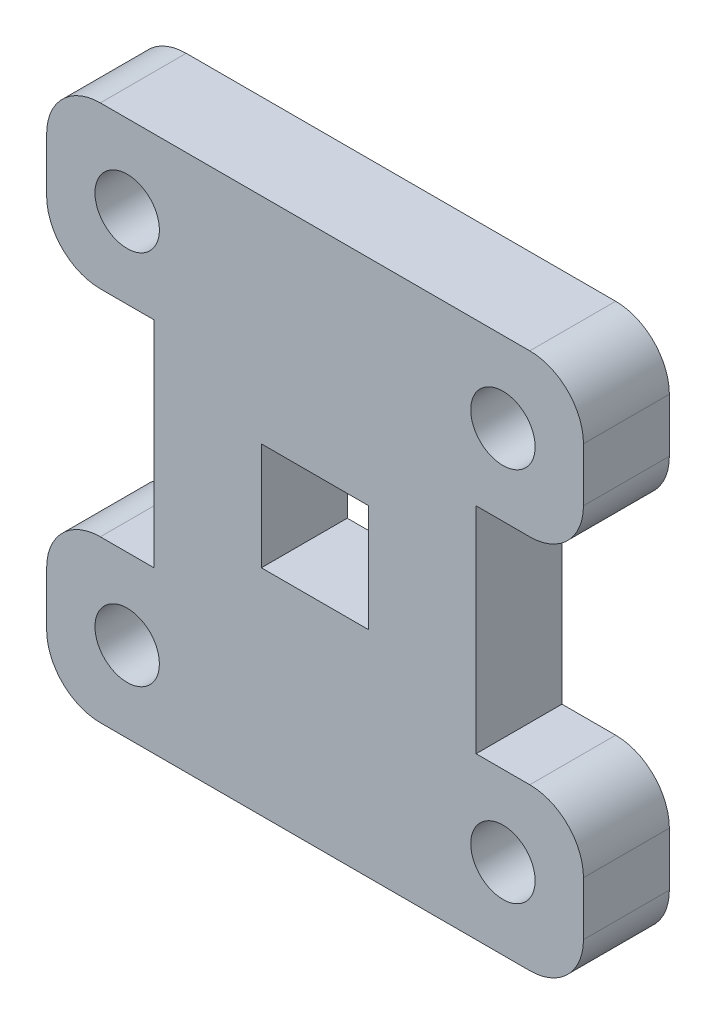
SolidWorks part; units mm, degrees
ref_plane "Front Plane" through (0, 0, 0) normal (0, 0, 1) x (1, 0, 0)
ref_plane "Top Plane" through (0, 0, 0) normal (0, 1, 0) x (1, 0, 0)
ref_plane "Right Plane" through (0, 0, 0) normal (1, 0, 0) x (0, 0, -1)
sketch "Sketch1" plane through (0, 0, 0) normal (0, 0, 1) x (1, 0, 0)
  line L0 (-40, 20) -> (-30, 20)
  line L3 (-40, 50) -> (40, 50)
  line L4 (50, 30) -> (50, 40)
  line L5 (-30, 20) -> (-30, -20)
  line L7 (-50, 30) -> (-50, 40)
  line L8 (-104.9282, 0) -> (85.9852, 0) construction
  line L9 (40, 20) -> (30, 20)
  line L10 (30, 20) -> (30, -20)
  line L11 (-40, -20) -> (-30, -20)
  line L12 (10, -10) -> (10, 10)
  line L13 (10, 10) -> (-10, 10)
  line L14 (-10, 10) -> (-10, -10)
  line L15 (10, -10) -> (-10, -10)
  line L16 (40, -20) -> (30, -20)
  line L17 (50, -30) -> (50, -40)
  line L18 (-40, -50) -> (40, -50)
  line L19 (-50, -30) -> (-50, -40)
  circle A0 centre (35, 35) radius 6
  circle A2 centre (-35, 35) radius 6
  arc A4 (40, 50) -> (50, 40) centre (40, 40) cw
  arc A5 (50, 30) -> (40, 20) centre (40, 30) cw
  arc A6 (-50, 30) -> (-40, 20) centre (-40, 30) ccw
  arc A7 (-50, 40) -> (-40, 50) centre (-40, 40) cw
  circle A8 centre (35, -35) radius 6
  circle A9 centre (-35, -35) radius 6
  arc A10 (50, -30) -> (40, -20) centre (40, -30) ccw
  arc A11 (40, -50) -> (50, -40) centre (40, -40) ccw
  arc A12 (-50, -40) -> (-40, -50) centre (-40, -40) ccw
  arc A13 (-50, -30) -> (-40, -20) centre (-40, -30) cw
  point P0 (0, 0)
  point P17 (50, 50)
  point P21 (50, 20)
  point P24 (-50, 20)
  point P27 (-50, 50)
  point P38 (-30, 0)
  point P39 (-10, 0)
  point P40 (10, 0)
  point P41 (30, 0)
  dimension "D3" = 12
  dimension "D6" = 10
  dimension "D1" = 100
  dimension "D2" = 20
  dimension "D4" = 15
  dimension "D5" = 15
  dimension "D7" = 15
  dimension "D8" = 15
  dimension "D9" = 20
  dimension "D10" = 20
  dimension "D11" = 10
  dimension "D12" = 20
  dimension "D13" = 10
extrude "Boss-Extrude1" add sketch "Sketch1" along normal blind 16
